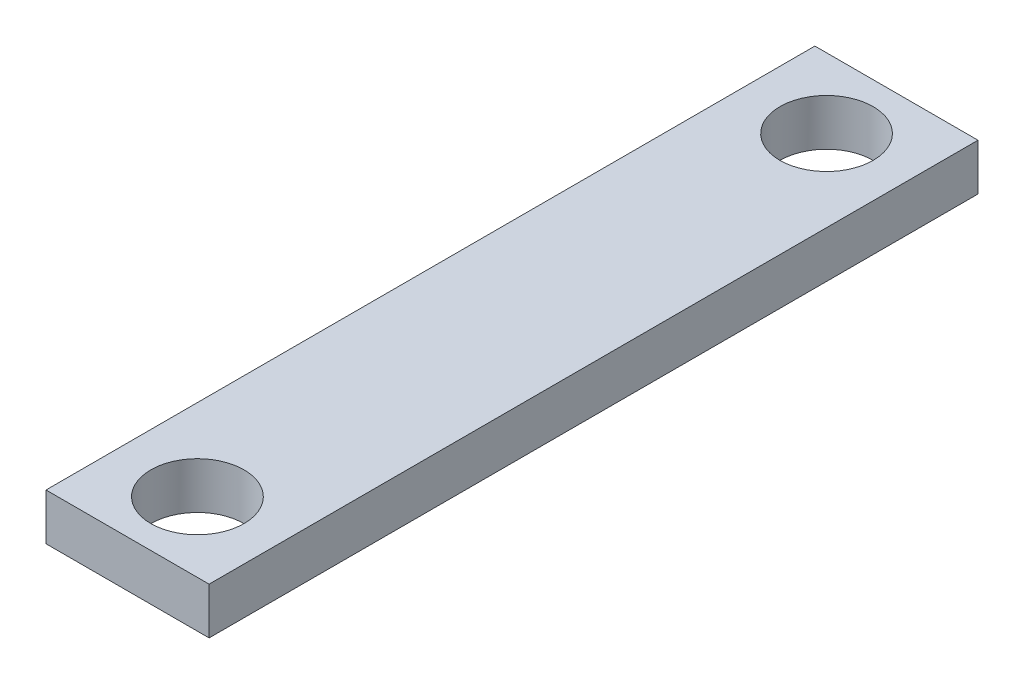
SolidWorks part; units mm, degrees
material "ABS PC"
ref_plane "Front Plane" through (0, 0, 0) normal (0, 0, 1) x (1, 0, 0)
ref_plane "Top Plane" through (0, 0, 0) normal (0, 1, 0) x (1, 0, 0)
ref_plane "Right Plane" through (0, 0, 0) normal (1, 0, 0) x (0, 0, -1)
sketch "Sketch1" plane through (0, 0, 0) normal (0, 0, 1) x (1, 0, 0)
  line L0 (0, 0) -> (0, 2)
  line L1 (0, 2) -> (7, 2)
  line L2 (7, 2) -> (7, 0)
  line L3 (7, 0) -> (0, 0)
  dimension "D1" = 2
  dimension "D2" = 7
extrude "Boss-Extrude1" add sketch "Sketch1" along normal blind 33
sketch "Sketch2" plane through (0, 2, 0) normal (0, 1, 0) x (1, 0, 0)
  line L0 (7, 0) -> (0, 0) construction
  line L1 (7, -33) -> (7, 0) construction
  line L2 (7, -33) -> (0, -33) construction
  circle A0 centre (3.5, -30) radius 2
  circle A1 centre (3.5, -3) radius 2
  dimension "D1" = 4
  dimension "D2" = 4
  dimension "D3" = 3
  dimension "D4" = 3.5
  dimension "D5" = 3.5
  dimension "D6" = 3
extrude "Cut-Extrude1" cut sketch "Sketch2" against normal up to next
